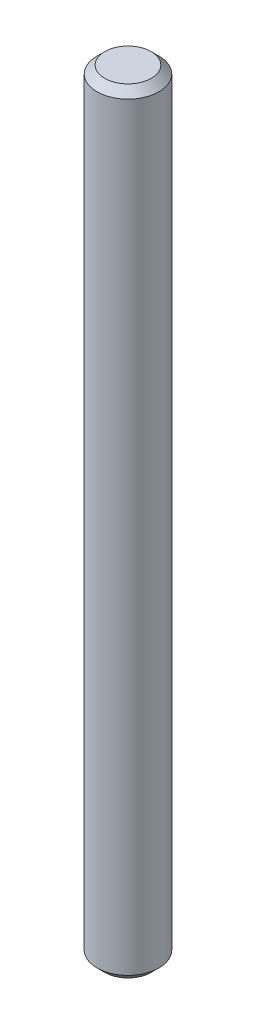
SolidWorks part; units mm, degrees
material "1060 Alloy"
ref_plane "Front Plane" through (0, 0, 0) normal (0, 0, 1) x (1, 0, 0)
ref_plane "Top Plane" through (0, 0, 0) normal (0, 1, 0) x (1, 0, 0)
ref_plane "Right Plane" through (0, 0, 0) normal (1, 0, 0) x (0, 0, -1)
sketch "Sketch1" plane through (0, 0, 0) normal (0, 1, 0) x (1, 0, 0)
  circle A0 centre (0, 0) radius 4
extrude "Boss-Extrude1" add sketch "Sketch1" along normal blind 100
chamfer "Chamfer1" distance 1 angle 45 2 edges at (0, 0, 4) (0, 100, 4)
